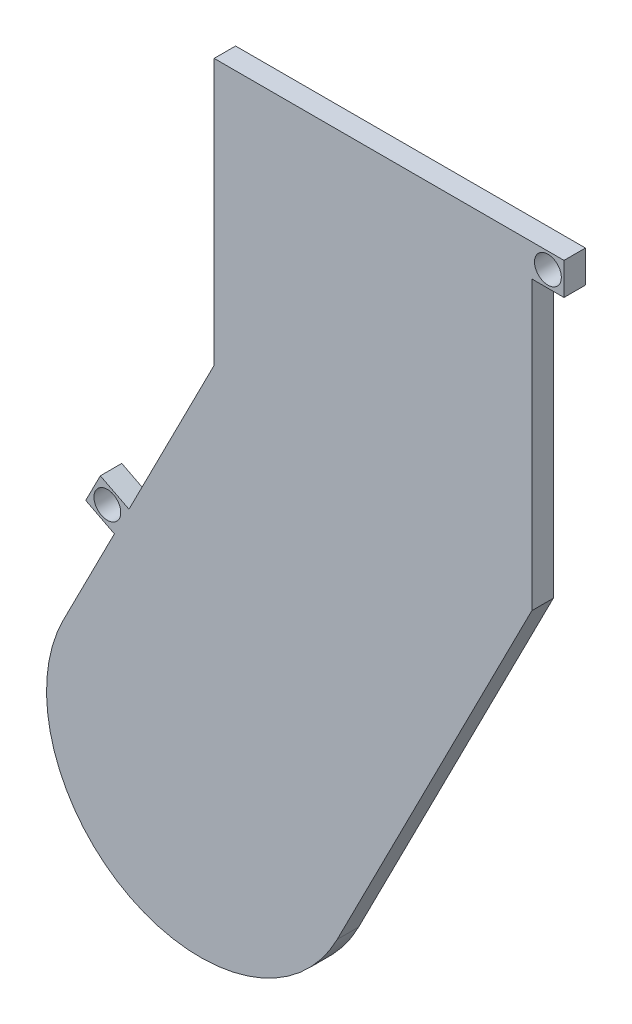
SolidWorks part; units mm, degrees
ref_plane "Front Plane" through (0, 0, 0) normal (0, 0, 1) x (1, 0, 0)
ref_plane "Top Plane" through (0, 0, 0) normal (0, 1, 0) x (1, 0, 0)
ref_plane "Right Plane" through (0, 0, 0) normal (1, 0, 0) x (0, 0, -1)
sketch "Sketch2" plane through (0, 0, 0) normal (0, 0, 1) x (1, 0, 0)
  line L0 (-95.4585, -102.5972) -> (-102.248, -99.1378)
  line L1 (-75.2786, 0) -> (0, 0)
  line L2 (0, -7.62) -> (0, -75.692)
  line L3 (0, -75.692) -> (-46.1254, -166.2183)
  line L4 (-75.2786, 0) -> (-75.2786, -62.992)
  line L5 (-75.2786, -62.992) -> (-95.4585, -102.5972)
  line L6 (-102.248, -99.1378) -> (-105.7074, -105.9273)
  line L7 (-105.7074, -105.9273) -> (-98.9179, -109.3867)
  line L8 (0, 0) -> (7.62, 0)
  line L9 (7.62, 0) -> (7.62, -7.62)
  line L10 (7.62, -7.62) -> (0, -7.62)
  line L11 (-98.9179, -109.3867) -> (-111.0258, -133.1499)
  arc A3 (-111.0258, -133.1499) -> (-46.1254, -166.2183) centre (-78.5756, -149.6841) ccw
  circle A4 centre (3.81, -3.81) radius 3.175
  circle A5 centre (-100.5829, -104.2623) radius 3.175
  dimension "D2" = 7.62
  dimension "D3" = 6.35
  dimension "D4" = 3.81
  dimension "D11" = 101.6
  dimension "D14" = 6.35
  dimension "D16" = 3.81
  dimension "D5" = 3.81
  dimension "D6" = 7.62
  dimension "D7" = 7.62
  dimension "D8" = 7.62
  dimension "D9" = 153
  dimension "D10" = 75.692
  dimension "D12" = 78.74
  dimension "D13" = 62.992
  dimension "D15" = 3.81
  dimension "D17" = 44.45
extrude "Boss-Extrude1" add sketch "Sketch2" along normal blind 5.08
